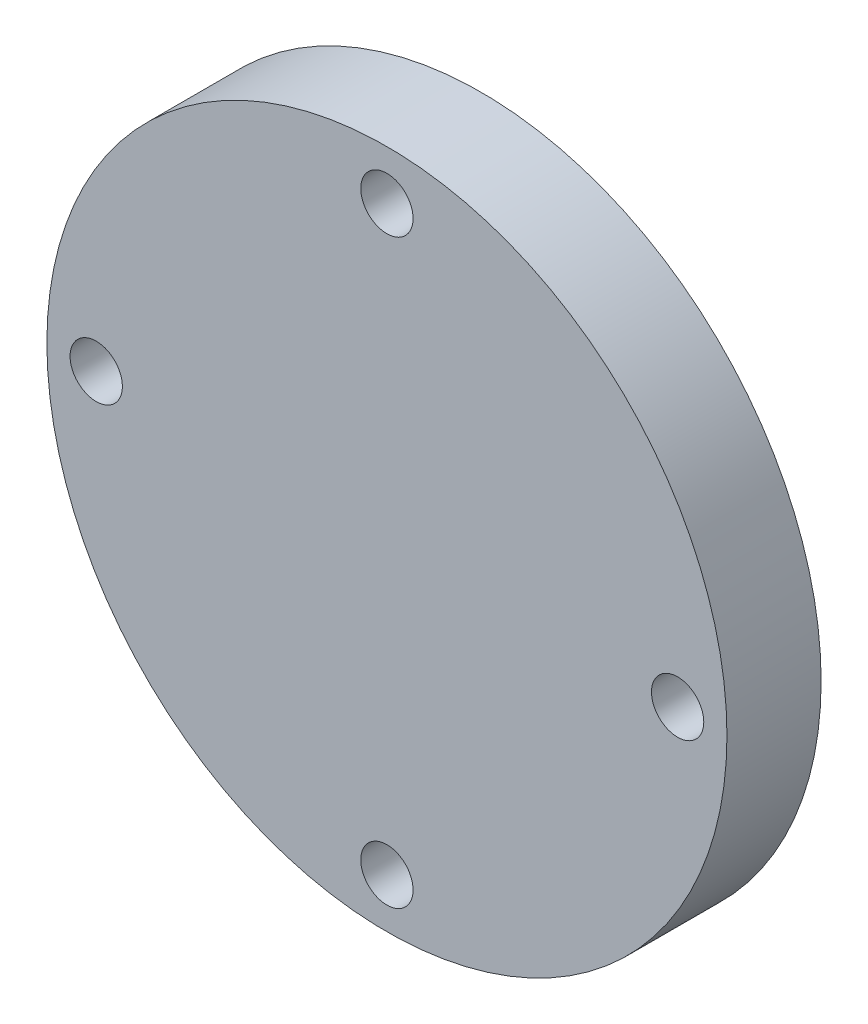
SolidWorks part; units mm, degrees
ref_plane "Front Plane" through (0, 0, 0) normal (0, 0, 1) x (1, 0, 0)
ref_plane "Top Plane" through (0, 0, 0) normal (0, 1, 0) x (1, 0, 0)
ref_plane "Right Plane" through (0, 0, 0) normal (1, 0, 0) x (0, 0, -1)
sketch "Sketch1" plane through (0, 0, 0) normal (0, 0, 1) x (1, 0, 0)
  circle A0 centre (0, 0) radius 21 construction
  circle A1 centre (0, 0) radius 21
  circle A2 centre (0, 0) radius 32.5
  dimension "D1" = 65
extrude "Boss-Extrude1" add sketch "Sketch1" along normal up to surface (1 mm away) from offset 1
sketch "Sketch2" plane through (0, 0, 2) normal (0, 0, 1) x (1, 0, 0)
  circle A1 centre (0, 0) radius 32.5
  circle A2 centre (0, 0) radius 32.5
  dimension "D1" = 0
extrude "Boss-Extrude2" add sketch "Sketch2" along normal blind 8
sketch "Sketch3" plane through (0, 0, 10) normal (0, 0, 1) x (1, 0, 0)
  circle A0 centre (0, 27.7831) radius 2.5
  circle A1 centre (0, 27.7831) radius 2.5 construction
  circle A2 centre (27.7831, 0) radius 2.5
  circle A3 centre (0, -27.7831) radius 2.5
  circle A4 centre (-27.7831, 0) radius 2.5
  point P13 (0, 0)
  dimension "D1" = 4
extrude "Cut-Extrude1" cut sketch "Sketch3" against normal through all
